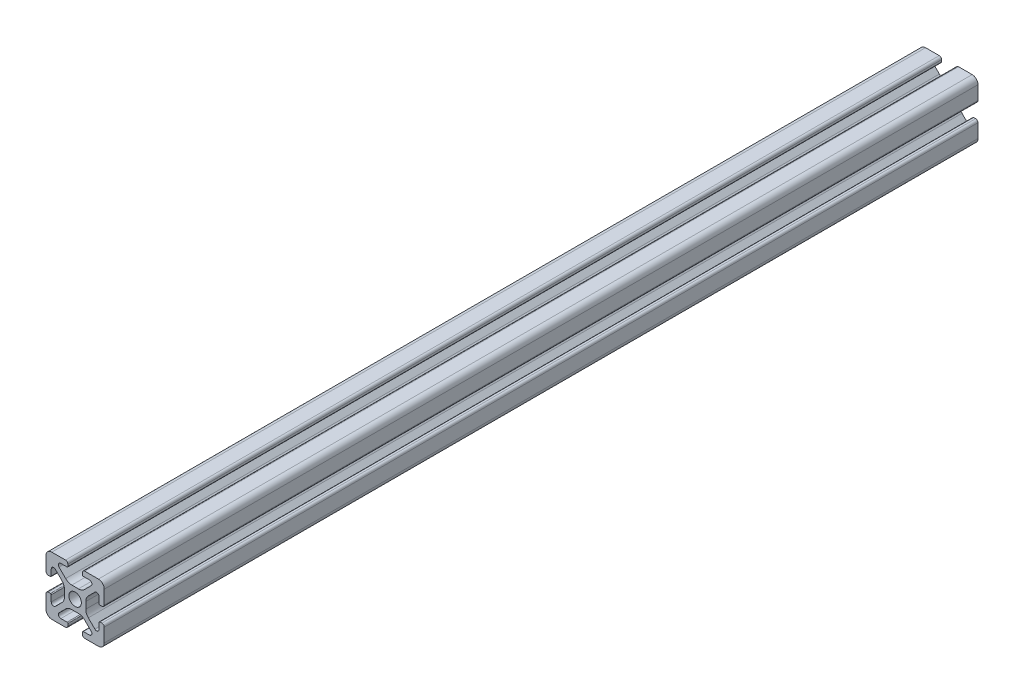
SolidWorks part; units mm, degrees
material "Alliage 1060"
ref_plane "Plan de face" through (0, 0, 0) normal (0, 0, 1) x (1, 0, 0)
ref_plane "Plan de dessus" through (0, 0, 0) normal (0, 1, 0) x (1, 0, 0)
ref_plane "Plan de droite" through (0, 0, 0) normal (1, 0, 0) x (0, 0, -1)
sketch "Esquisse1" plane through (0, 0, 0) normal (0, 0, 1) x (1, 0, 0)
  line L108 (-3.2559, 4.5287) -> (-5.5062, 6.779)
  line L109 (-4.9176, 8.2) -> (-2.8, 8.2)
  line L110 (-2.5, 8.5) -> (-2.5, 9.2)
  line L111 (-3.3, 10) -> (-8, 10)
  line L112 (-10, 8) -> (-10, 3.3)
  line L113 (-9.2, 2.5) -> (-8.5, 2.5)
  line L114 (-8.2, 2.8) -> (-8.2, 4.9176)
  line L115 (-6.779, 5.5062) -> (-4.5287, 3.2559)
  line L116 (-3.65, 1.1346) -> (-3.65, -1.1346)
  line L117 (-4.5287, -3.2559) -> (-6.779, -5.5062)
  line L118 (-8.2, -4.9176) -> (-8.2, -2.8)
  line L119 (-8.5, -2.5) -> (-9.2, -2.5)
  line L120 (-10, -3.3) -> (-10, -8)
  line L121 (-8, -10) -> (-3.3, -10)
  line L122 (-2.5, -9.2) -> (-2.5, -8.5)
  line L123 (-2.8, -8.2) -> (-4.9176, -8.2)
  line L124 (-5.5062, -6.779) -> (-3.2559, -4.5287)
  line L125 (-1.1346, -3.65) -> (1.1346, -3.65)
  line L126 (3.2559, -4.5287) -> (5.5062, -6.779)
  line L127 (4.9176, -8.2) -> (2.8, -8.2)
  line L128 (2.5, -8.5) -> (2.5, -9.2)
  line L129 (3.3, -10) -> (8, -10)
  line L130 (10, -8) -> (10, -3.3)
  line L131 (9.2, -2.5) -> (8.5, -2.5)
  line L132 (8.2, -2.8) -> (8.2, -4.9176)
  line L133 (6.779, -5.5062) -> (4.5287, -3.2559)
  line L134 (3.65, -1.1346) -> (3.65, 1.1346)
  line L135 (4.5287, 3.2559) -> (6.779, 5.5062)
  line L136 (8.2, 4.9176) -> (8.2, 2.8)
  line L137 (8.5, 2.5) -> (9.2, 2.5)
  line L138 (10, 3.3) -> (10, 8)
  line L139 (8, 10) -> (3.3, 10)
  line L140 (2.5, 9.2) -> (2.5, 8.5)
  line L141 (2.8, 8.2) -> (4.9176, 8.2)
  line L142 (5.5062, 6.779) -> (3.2559, 4.5287)
  line L143 (1.1346, 3.65) -> (-1.1346, 3.65)
  arc A42 (-2.15, 0) -> (2.15, 0) centre (0, 0) ccw
  arc A43 (2.15, 0) -> (-2.15, 0) centre (0, 0) ccw
  arc A108 (-4.9176, 8.2) -> (-5.5062, 6.779) centre (-4.9176, 7.3676) ccw
  arc A109 (-2.8, 8.2) -> (-2.5, 8.5) centre (-2.8, 8.5) ccw
  arc A110 (-2.5, 9.2) -> (-3.3, 10) centre (-3.3, 9.2) ccw
  arc A111 (-8, 10) -> (-10, 8) centre (-8, 8) ccw
  arc A112 (-10, 3.3) -> (-9.2, 2.5) centre (-9.2, 3.3) ccw
  arc A113 (-8.5, 2.5) -> (-8.2, 2.8) centre (-8.5, 2.8) ccw
  arc A114 (-6.779, 5.5062) -> (-8.2, 4.9176) centre (-7.3676, 4.9176) ccw
  arc A115 (-3.65, 1.1346) -> (-4.5287, 3.2559) centre (-6.65, 1.1346) ccw
  arc A116 (-4.5287, -3.2559) -> (-3.65, -1.1346) centre (-6.65, -1.1346) ccw
  arc A117 (-8.2, -4.9176) -> (-6.779, -5.5062) centre (-7.3676, -4.9176) ccw
  arc A118 (-8.2, -2.8) -> (-8.5, -2.5) centre (-8.5, -2.8) ccw
  arc A119 (-9.2, -2.5) -> (-10, -3.3) centre (-9.2, -3.3) ccw
  arc A120 (-10, -8) -> (-8, -10) centre (-8, -8) ccw
  arc A121 (-3.3, -10) -> (-2.5, -9.2) centre (-3.3, -9.2) ccw
  arc A122 (-2.5, -8.5) -> (-2.8, -8.2) centre (-2.8, -8.5) ccw
  arc A123 (-5.5062, -6.779) -> (-4.9176, -8.2) centre (-4.9176, -7.3676) ccw
  arc A124 (-1.1346, -3.65) -> (-3.2559, -4.5287) centre (-1.1346, -6.65) ccw
  arc A125 (3.2559, -4.5287) -> (1.1346, -3.65) centre (1.1346, -6.65) ccw
  arc A126 (4.9176, -8.2) -> (5.5062, -6.779) centre (4.9176, -7.3676) ccw
  arc A127 (2.8, -8.2) -> (2.5, -8.5) centre (2.8, -8.5) ccw
  arc A128 (2.5, -9.2) -> (3.3, -10) centre (3.3, -9.2) ccw
  arc A129 (8, -10) -> (10, -8) centre (8, -8) ccw
  arc A130 (10, -3.3) -> (9.2, -2.5) centre (9.2, -3.3) ccw
  arc A131 (8.5, -2.5) -> (8.2, -2.8) centre (8.5, -2.8) ccw
  arc A132 (6.779, -5.5062) -> (8.2, -4.9176) centre (7.3676, -4.9176) ccw
  arc A133 (3.65, -1.1346) -> (4.5287, -3.2559) centre (6.65, -1.1346) ccw
  arc A134 (4.5287, 3.2559) -> (3.65, 1.1346) centre (6.65, 1.1346) ccw
  arc A135 (8.2, 4.9176) -> (6.779, 5.5062) centre (7.3676, 4.9176) ccw
  arc A136 (8.2, 2.8) -> (8.5, 2.5) centre (8.5, 2.8) ccw
  arc A137 (9.2, 2.5) -> (10, 3.3) centre (9.2, 3.3) ccw
  arc A138 (10, 8) -> (8, 10) centre (8, 8) ccw
  arc A139 (3.3, 10) -> (2.5, 9.2) centre (3.3, 9.2) ccw
  arc A140 (2.5, 8.5) -> (2.8, 8.2) centre (2.8, 8.5) ccw
  arc A141 (5.5062, 6.779) -> (4.9176, 8.2) centre (4.9176, 7.3676) ccw
  arc A142 (1.1346, 3.65) -> (3.2559, 4.5287) centre (1.1346, 6.65) ccw
  arc A143 (-3.2559, 4.5287) -> (-1.1346, 3.65) centre (-1.1346, 6.65) ccw
extrude "Boss.-Extru.1" add sketch "Esquisse1" along normal blind 300
sketch "Esquisse2" [suppressed] plane through (10, 0, 0) normal (1, 0, 0) x (0, 0, -1)
  line L0 (-120, 8) -> (-120, -8) construction
  line L1 (0, 0) -> (-120, 0) construction
  circle A0 centre (-105, 0) radius 6
  circle A1 centre (-15, 0) radius 6
  dimension "D2" = 12
  dimension "D4" = 12
  dimension "D1" = 15
  dimension "D3" = 15
extrude "Enlèv. mat.-Extru.1" [suppressed] cut sketch "Esquisse2" against normal blind 7
sketch "Esquisse3" [suppressed] plane through (3, 0, 0) normal (1, 0, 0) x (0, 0, -1)
  circle A0 centre (-105, 0) radius 2.5
  circle A1 centre (-15, 0) radius 2.5
  arc A2 (-100.816, -4.3005) -> (-100.816, 4.3005) centre (-105, 0) ccw construction
  arc A3 (-10.816, -4.3005) -> (-10.816, 4.3005) centre (-15, 0) ccw construction
  dimension "D1" = 5
extrude "Enlèv. mat.-Extru.2" [suppressed] cut sketch "Esquisse3" against normal through all
equation "\"Length\" = 300"
equation "\"D1@Boss.-Extru.1\"=\"Length\""
